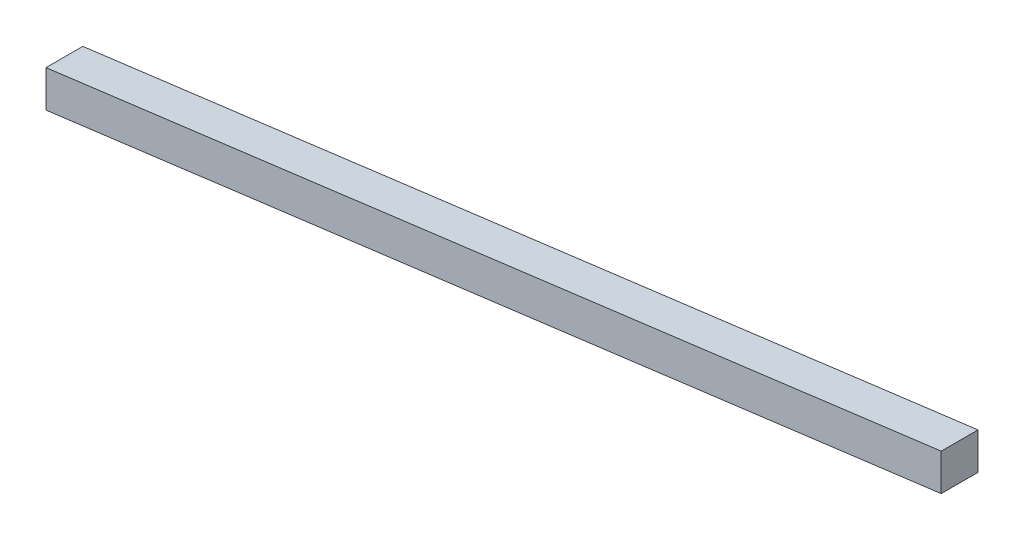
SolidWorks part; units mm, degrees
ref_plane "Front Plane" through (0, 0, 0) normal (1, 0, 0) x (0, 1, 0)
ref_plane "Top Plane" through (0, 0, 0) normal (0, 0, 1) x (0, 1, 0)
ref_plane "Right Plane" through (0, 0, 0) normal (0, 1, 0) x (-1, 0, 0)
sketch "Sketch1" plane through (0, 0, 0) normal (0, 0, 1) x (0, 1, 0)
  line L0 (-12.4164, 73.0062) -> (-6.4164, 73.0062)
  line L1 (-6.4164, 73.0062) -> (12.4164, -73.0062)
  line L2 (12.4164, -73.0062) -> (6.4164, -73.0062)
  line L3 (-12.4164, 73.0062) -> (6.4164, -73.0062)
extrude "Boss-Extrude1" add sketch "Sketch1" along normal blind 6
